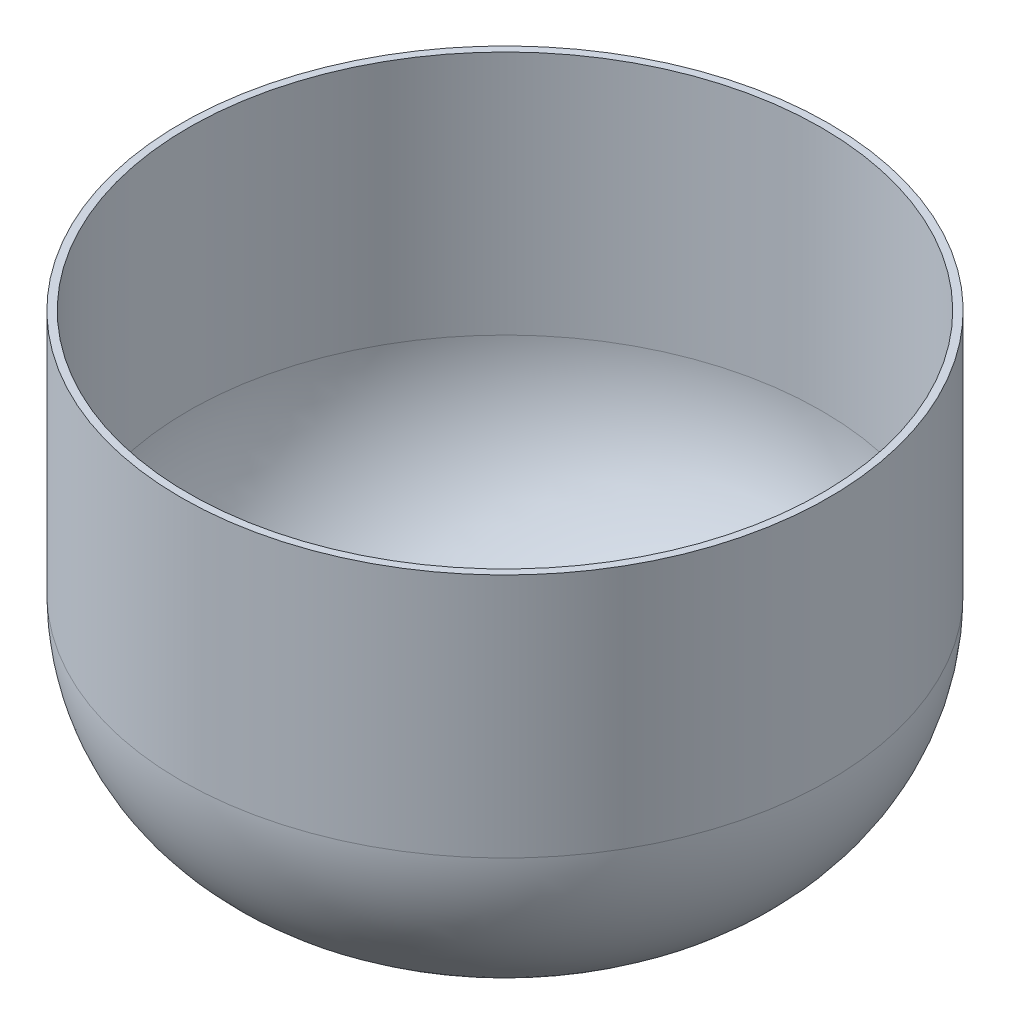
SolidWorks part; units mm, degrees
ref_plane "Ön Düzlem" through (0, 0, 0) normal (0, 0, 1) x (1, 0, 0)
ref_plane "Üst Düzlem" through (0, 0, 0) normal (0, 1, 0) x (1, 0, 0)
ref_plane "Sağ Düzlem" through (0, 0, 0) normal (1, 0, 0) x (0, 0, -1)
sketch "Çizim1" plane through (0, 0, 0) normal (0, 0, 1) x (1, 0, 0)
  line L0 (0, 0) -> (0, 19.985) construction
  line L1 (-64.5, 44.2768) -> (-64.5, -5.6632)
  line L2 (-64.5, -5.6632) -> (-47.5, -5.6632) construction
  line L3 (-47.5, -5.6632) -> (-47.5, -24.0957) construction
  line L4 (-66, 44.2768) -> (-66, -5.6632)
  line L6 (-64.5, 44.2768) -> (-66, 44.2768)
  line L7 (-42.66, -31.0832) -> (-42.66, -39.5832) construction
  line L8 (-42.66, -39.5832) -> (-41.66, -39.5832)
  line L10 (-41.66, -39.5832) -> (-41.66, -40.3332)
  line L11 (-42.66, -41.0832) -> (-42.66, -40.3332)
  line L12 (-42.66, -40.3332) -> (-41.66, -40.3332)
  line L14 (-42.66, -41.0832) -> (-41.66, -41.0832) construction
  arc A0 (-64.5, -5.6632) -> (-47.7299, -37.9056) centre (-25.12, -5.6632) ccw
  arc A1 (-66, -5.6632) -> (-48.6075, -39.1222) centre (-25.12, -5.6632) ccw
  arc A2 (-47.7299, -37.9056) -> (-42.66, -39.5832) centre (-42.66, -31.0832) ccw
  arc A3 (-48.6075, -39.1222) -> (-42.66, -41.0832) centre (-42.66, -31.0832) ccw
  arc A4 (-66, -5.6632) -> (-48.3525, -39.2998) centre (-25.12, -5.6632) ccw construction
  arc A5 (-48.6246, -39.1095) -> (-42.66, -41.0832) centre (-42.66, -31.0832) ccw construction
  arc A6 (-64.5, -5.6632) -> (-47.5, -38.0656) centre (-25.12, -5.6632) ccw construction
  dimension "D3" = 17
  dimension "D6" = 17
  dimension "D1" = 49.94
  dimension "D2" = 64.5
  dimension "D4" = 25.12
  dimension "D5" = 1.5
  dimension "D7" = 42.66
  dimension "D8" = 25.42
  dimension "D9" = 1
  dimension "D11" = 0.75
  dimension "D10" = 1.5
revolve "Döndür1" add sketch "Çizim1" angle 360 about L0
